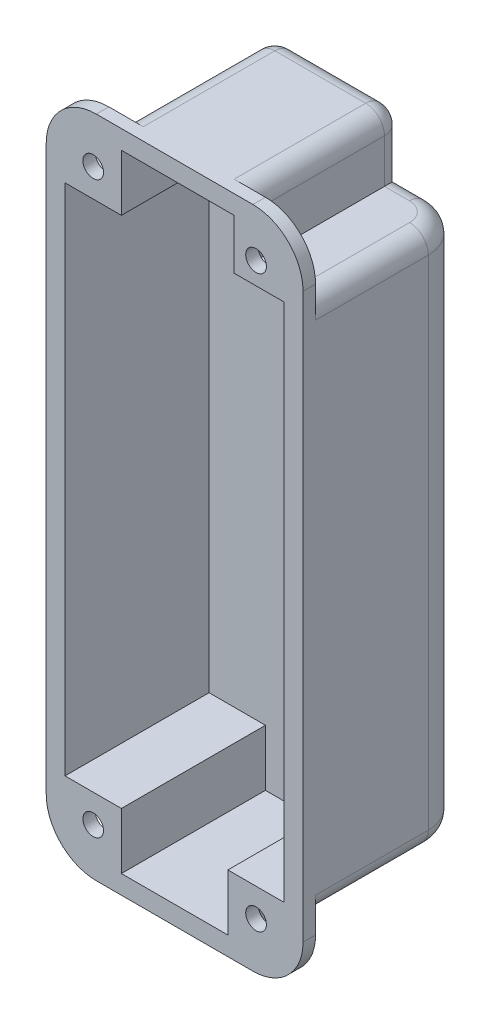
SolidWorks part; units mm, degrees
ref_plane "前视基准面" through (0, 0, 0) normal (0, 0, 1) x (1, 0, 0)
ref_plane "上视基准面" through (0, 0, 0) normal (0, 1, 0) x (1, 0, 0)
ref_plane "右视基准面" through (0, 0, 0) normal (1, 0, 0) x (0, 0, -1)
sketch "草图2" plane through (0, 0, 0) normal (0, 0, 1) x (1, 0, 0)
  line L1 (0, 0) -> (35, 0)
  line L2 (0, 0) -> (0, 100)
  line L3 (0, 100) -> (35, 100)
  line L4 (35, 0) -> (35, 100)
  line L5 (-3, -3) -> (38, -3)
  line L6 (-3, -3) -> (-3, 103)
  line L7 (-3, 103) -> (38, 103)
  line L8 (38, -3) -> (38, 103)
  line L9 (0, 100) -> (9, 100)
  line L10 (0, 100) -> (0, 91)
  line L11 (0, 91) -> (9, 91)
  line L12 (9, 100) -> (9, 91)
  line L13 (0, 100) -> (7.5, 100)
  line L14 (0, 100) -> (0, 92.5)
  line L15 (0, 92.5) -> (7.5, 92.5)
  line L16 (7.5, 100) -> (7.5, 92.5)
  line L17 (35, 100) -> (27, 100)
  line L18 (35, 100) -> (35, 92)
  line L19 (35, 92) -> (27, 92)
  line L20 (27, 100) -> (27, 92)
  line L21 (35, 100) -> (28, 100)
  line L22 (35, 100) -> (35, 93)
  line L23 (35, 93) -> (28, 93)
  line L24 (28, 100) -> (28, 93)
  line L25 (0, 0) -> (9, 0)
  line L26 (0, 0) -> (0, 9)
  line L27 (0, 9) -> (9, 9)
  line L28 (9, 0) -> (9, 9)
  line L29 (0, 0) -> (7.5, 0)
  line L30 (0, 0) -> (0, 7.5)
  line L31 (0, 7.5) -> (7.5, 7.5)
  line L32 (7.5, 0) -> (7.5, 7.5)
  line L33 (35, 0) -> (26, 0)
  line L34 (35, 0) -> (35, 9)
  line L35 (35, 9) -> (26, 9)
  line L36 (26, 0) -> (26, 9)
  line L37 (35, 0) -> (27.5, 0)
  line L38 (35, 0) -> (35, 7.5)
  line L39 (35, 7.5) -> (27.5, 7.5)
  line L40 (27.5, 0) -> (27.5, 7.5)
  circle A0 centre (4.5, 95.5) radius 1.65
  circle A1 centre (30.5, 95.5) radius 1.65
  circle A2 centre (4.5, 4.5) radius 1.65
  circle A3 centre (30.5, 4.5) radius 1.65
  dimension "D10" = 4.5
  dimension "D18" = 4.5
  dimension "D24" = 4.5
  dimension "D30" = 3
  dimension "D1" = 35
  dimension "D2" = 100
  dimension "D3" = 106
  dimension "D4" = 41
  dimension "D5" = 3
  dimension "D6" = 3
  dimension "D7" = 9
  dimension "D8" = 35
  dimension "D9" = 9
  dimension "D11" = 4.5
  dimension "D12" = 7.5
  dimension "D13" = 7.5
  dimension "D14" = 8
  dimension "D15" = 8
  dimension "D16" = 7
  dimension "D17" = 7
  dimension "D19" = 4.5
  dimension "D20" = 9
  dimension "D21" = 9
  dimension "D22" = 7.5
  dimension "D23" = 7.5
  dimension "D25" = 4.5
  dimension "D26" = 9
  dimension "D27" = 9
  dimension "D28" = 7.5
  dimension "D29" = 7.5
  dimension "D31" = 4.5
  dimension "D32" = 4.5
extrude "凸台-拉伸3" add sketch "草图2" along normal blind 23 contours L5 L8 L7 L6 L4 L33 L1 L25 L2 L26 L10 L3 L9 L17 L18 L34 | L32 L25 L28 L27 L26 L31 | L24 L3 L20 L19 L4 L23 | A0 | A2 | A3 | L38 L39 L40 L37 | A1
sketch "草图5" plane through (0, 0, 23) normal (0, 0, 1) x (1, 0, 0)
  line L2 (26, 9) -> (35, 9)
  line L3 (26, 9) -> (26, 0)
  line L4 (26, 0) -> (35, 0)
  line L5 (35, 9) -> (35, 0)
  circle A0 centre (30.5, 4.5) radius 1.65
  dimension "D3" = 4.5
  dimension "D1" = 9
  dimension "D2" = 9
  dimension "D4" = 4.5
extrude "切除-拉伸2" cut sketch "草图5" against normal through all contours A0
sketch "草图6" plane through (0, 0, 0) normal (0, 0, -1) x (-1, 0, 0)
  line L1 (-38, 103) -> (3, 103)
  line L2 (-38, 103) -> (-38, -3)
  line L3 (-38, -3) -> (3, -3)
  line L4 (3, 103) -> (3, -3)
extrude "凸台-拉伸4" add sketch "草图6" along normal blind 3
sketch "草图7" plane through (0, 0, 23) normal (0, 0, 1) x (1, 0, 0)
  line L1 (-3, 103) -> (7.5, 103)
  line L2 (-3, 103) -> (-3, 92.5)
  line L3 (-3, 92.5) -> (7.5, 92.5)
  line L4 (7.5, 103) -> (7.5, 92.5)
  line L5 (38, 103) -> (28, 103)
  line L6 (38, 103) -> (38, 93)
  line L7 (38, 93) -> (28, 93)
  line L8 (28, 103) -> (28, 93)
  line L9 (-3, -3) -> (7.5, -3)
  line L10 (-3, -3) -> (-3, 7.5)
  line L11 (-3, 7.5) -> (7.5, 7.5)
  line L12 (7.5, -3) -> (7.5, 7.5)
  line L13 (38, -3) -> (27.5, -3)
  line L14 (38, -3) -> (38, 7.5)
  line L15 (38, 7.5) -> (27.5, 7.5)
  line L16 (27.5, -3) -> (27.5, 7.5)
  dimension "D1" = 10.5
  dimension "D2" = 10.5
  dimension "D3" = 10
  dimension "D4" = 10
  dimension "D5" = 10.5
  dimension "D6" = 10.5
  dimension "D7" = 10.5
  dimension "D8" = 10.5
extrude "切除-拉伸3" cut sketch "草图7" against normal through all from offset 2 contours L10 L9 L12 L11 | L14 L13 L16 L15 | L2 L1 L4 L3 | L6 L5 L8 L7 offset against normal yes
fillet "圆角1" radius 8 4 edges at (38, 103, 22) (-3, 103, 22) (38, -3, 22) (-3, -3, 22)
fillet "圆角2" radius 6 2 edges at (-3, 50, -3) (38, 50.25, -3)
fillet "圆角3" radius 3 22 edges at (5.25, 7.5, -3) (-1.2426, 7.5, -1.2426) (38, 93, 12) (36.2426, 93, -1.2426) (-3, 92.5, 12) (-1.2426, 92.5, -1.2426) (7.5, -3, 9) (17.5, -3, -3) (7.5, 2.25, -3) (-3, 7.5, 12) (30, 93, -3) (28, 98, -3) (5.25, 92.5, -3) (7.5, 97.75, -3) (17.75, 103, -3) (7.5, 103, 9) (28, 103, 9) (29.75, 7.5, -3) (36.2426, 7.5, -1.2426) (27.5, -3, 9) (27.5, 2.25, -3) (38, 7.5, 12)
